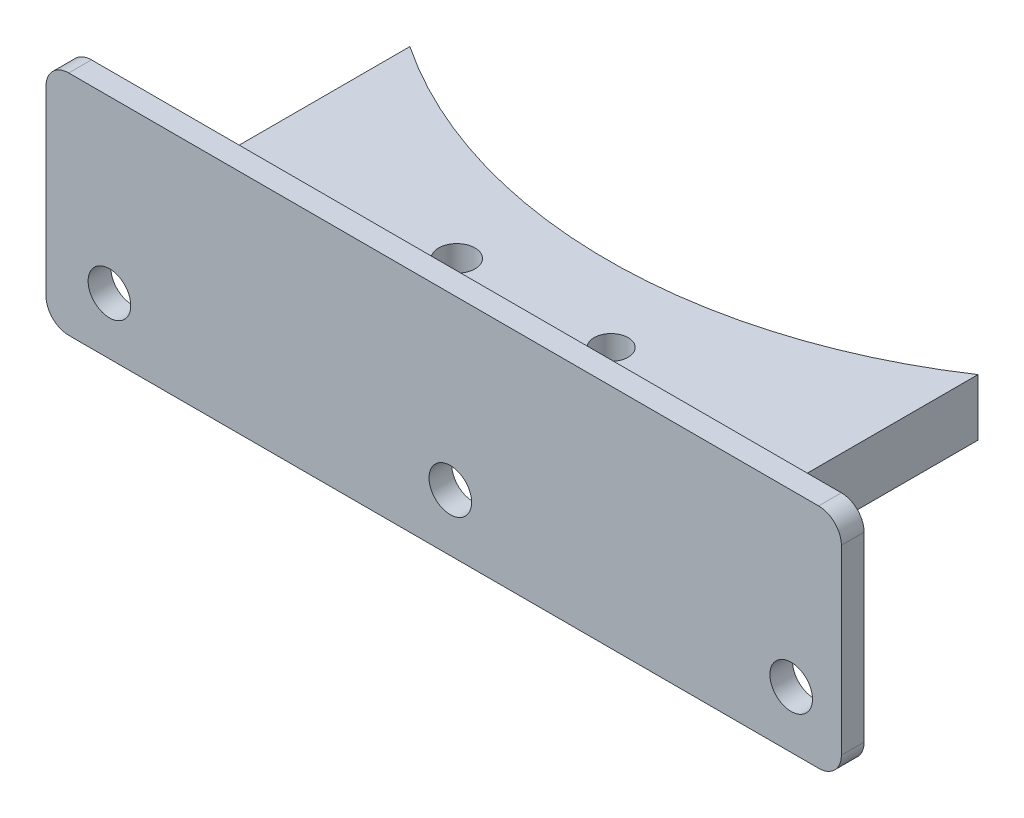
SolidWorks part; units mm, degrees
material "PET"
ref_plane "Front Plane" through (0, 0, 0) normal (0, 0, 1) x (1, 0, 0)
ref_plane "Top Plane" through (0, 0, 0) normal (0, 1, 0) x (1, 0, 0)
ref_plane "Right Plane" through (0, 0, 0) normal (1, 0, 0) x (0, 0, -1)
sketch "Sketch1" plane through (0, 0, 0) normal (0, 0, 1) x (1, 0, 0)
  line L1 (-44.45, -12.7) -> (44.45, -12.7)
  line L2 (-44.45, -12.7) -> (-44.45, 12.7)
  line L3 (-44.45, 12.7) -> (44.45, 12.7)
  line L4 (44.45, -12.7) -> (44.45, 12.7)
  line L5 (-44.45, -12.7) -> (44.45, 12.7) construction
  line L6 (-44.45, 12.7) -> (44.45, -12.7) construction
  point P0 (0, 0)
  point P5 (0, 0)
  dimension "D1" = 88.9
  dimension "D2" = 25.4
extrude "Boss-Extrude1" add sketch "Sketch1" along normal blind 2.54
sketch "Sketch2" plane through (0, 0, 0) normal (0, 1, 0) x (1, 0, 0)
  line L0 (0, 0) -> (0, 73.025) construction
  line L1 (44.45, 0) -> (-44.45, 0) construction
  line L2 (0, 73.025) -> (-8.6199, 7.55) construction
  line L3 (0, 73.025) -> (8.6199, 7.55) construction
  line L4 (-31.75, 0) -> (-31.75, 25.4296)
  line L5 (-31.75, 0) -> (0, 0)
  line L6 (0, 0) -> (31.75, 0)
  line L7 (31.75, 0) -> (31.75, 25.4296)
  circle A0 centre (0, 73.025) radius 73.025 construction
  circle A1 centre (0, 73.025) radius 57.2135 construction
  circle A2 centre (0, 73.025) radius 66.04 construction
  circle A3 centre (-8.6199, 7.55) radius 2.032
  circle A4 centre (8.6199, 7.55) radius 1.905
  arc A5 (-31.75, 25.4296) -> (31.75, 25.4296) centre (0, 73.025) ccw
  point P17 (-32.1287, 25.4296)
  point P18 (31.1999, 25.0672)
  dimension "D1" = 146.05
  dimension "D2" = 114.427
  dimension "D3" = 132.08
  dimension "D4" = 4.064
  dimension "D5" = 3.81
  dimension "D6" = 7.5
  dimension "D7" = 7.5
  dimension "D8" = 63.5
extrude "Boss-Extrude2" add sketch "Sketch2" along normal blind 6.35
sketch "Sketch3" plane through (0, 0, 0) normal (0, 0, -1) x (-1, 0, 0)
  line L0 (-44.45, -6.35) -> (44.45, -6.35) construction
  line L1 (-44.45, -12.7) -> (-44.45, 12.7) construction
  line L2 (44.45, 12.7) -> (44.45, -12.7) construction
  line L3 (44.45, -12.7) -> (-44.45, -12.7) construction
  circle A0 centre (-38.8384, -6.35) radius 2.3812
  circle A1 centre (-0.7384, -6.35) radius 2.3813
  circle A2 centre (37.3616, -6.35) radius 2.3812
  point P14 (0, -6.35)
  dimension "D2" = 4.7625
  dimension "D1" = 6.35
  dimension "D3" = 38.1
  dimension "D4" = 38.1
extrude "Cut-Extrude1" cut sketch "Sketch3" against normal through all
fillet "Fillet1" radius 2.54 7 edges at (31.75, 3.175, 0) (-31.75, 3.175, 0) (0, 6.35, 0) (44.45, -12.7, 1.27) (44.45, 12.7, 1.27) (-44.45, 12.7, 1.27) (-44.45, -12.7, 1.27)
